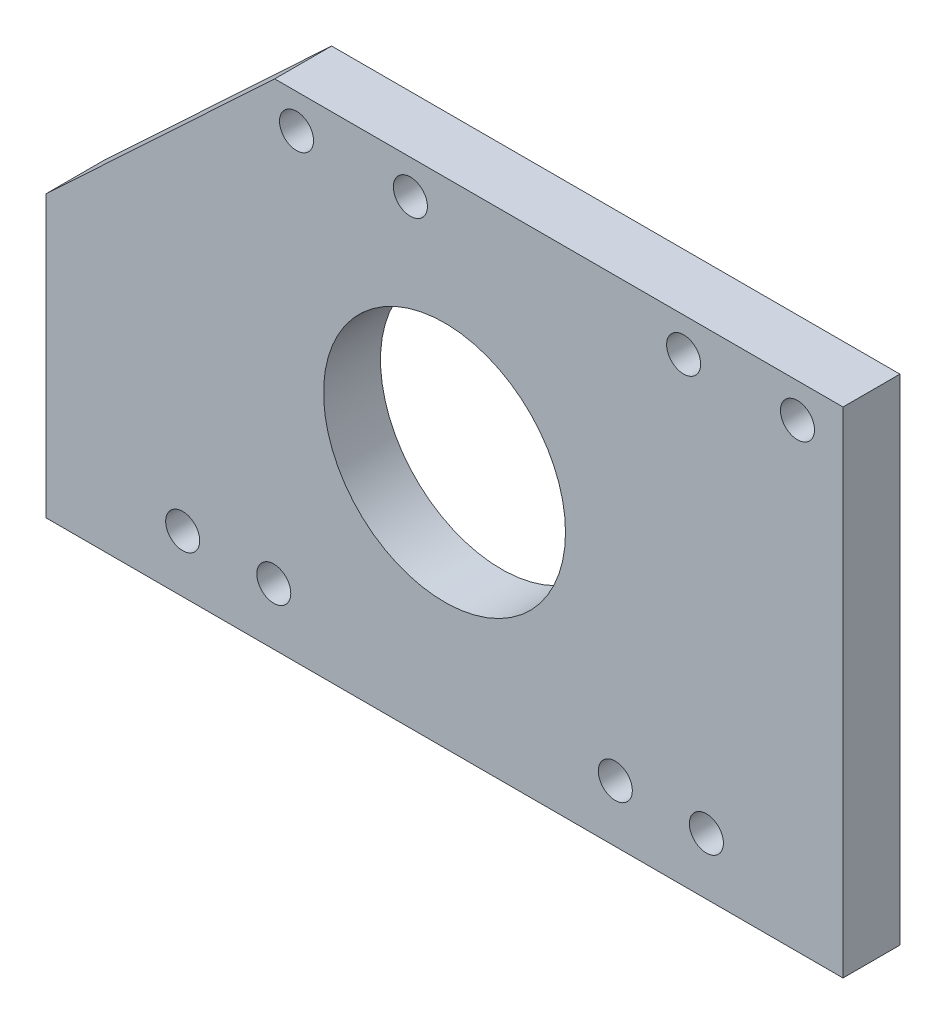
SolidWorks part; units mm, degrees
ref_plane "Front Plane" through (0, 0, 0) normal (0, 0, 1) x (1, 0, 0)
ref_plane "Top Plane" through (0, 0, 0) normal (0, 1, 0) x (1, 0, 0)
ref_plane "Right Plane" through (0, 0, 0) normal (1, 0, 0) x (0, 0, -1)
sketch "Sketch1" plane through (0, 0, 0) normal (0, 0, 1) x (1, 0, 0)
  line L0 (82.55, 0) -> (-82.55, 0)
  line L1 (127, -27.5819) -> (-127, -27.5819)
  line L2 (127, -27.5819) -> (127, 27.5819)
  line L3 (127, 27.5819) -> (-127, 27.5819)
  line L4 (-127, -27.5819) -> (-127, 27.5819)
  line L5 (127, -27.5819) -> (-127, 27.5819) construction
  line L6 (127, 27.5819) -> (-127, -27.5819) construction
  circle A0 centre (-82.55, 0) radius 13.4937
  circle A1 centre (82.55, 0) radius 13.4937
  point P0 (0, 0)
  point P12 (0, 0)
  dimension "D3" = 26.9875
  dimension "D4" = 26.9875
  dimension "D1" = 254
  dimension "D2" = 55.1637
  dimension "D5" = 165.1
extrude "Boss-Extrude1" add sketch "Sketch1" along normal blind 6.35
hole_wizard "#6 Clearance Hole1" positions "Sketch2" profile "Sketch3" hole size "#6" standard "ANSI Inch" end condition through all
sketch "Sketch2" plane through (0, 0, 6.35) normal (0, 0, 1) x (1, 0, 0)
  line L0 (-111.76, -21.2319) -> (-101.6, -21.2319)
  line L2 (-63.5, -21.2319) -> (-53.34, -21.2319)
  line L4 (127, -27.5819) -> (-127, -27.5819) construction
  line L5 (-127, -27.5819) -> (-127, 27.5819) construction
  point P0 (-111.76, -21.2319)
  point P2 (-101.6, -21.2319)
  point P4 (-63.5, -21.2319)
  point P6 (-53.34, -21.2319)
  dimension "D1" = 6.35
  dimension "D2" = 6.35
  dimension "D3" = 10.16
  dimension "D4" = 10.16
  dimension "D5" = 15.24
  dimension "D6" = 63.5
sketch "Sketch3" plane through (-111.76, -21.2319, 6.35) normal (1, 0, 0) x (0, -1, 0)
  line L0 (0, 0) -> (0, 6.35)
  line L1 (0, 6.35) -> (1.8986, 6.35)
  line L2 (1.8986, 6.35) -> (1.8986, 0)
  line L5 (1.8986, 0) -> (0, 0)
  line L11 (0, -6.35) -> (0, 107.95) construction
  dimension "Thru Hole Dia." = 3.7973
  dimension "Thru Hole Depth" = 6.35
ref_plane "Plane1" through (0, 0, 0) normal (-1, 0, 0) x (0, 0, 1)
mirror "Mirror1" about plane through (0, 0, 0) normal (-1, 0, 0) of "#6 Clearance Hole1"
sketch "Sketch4" plane through (0, 0, 6.35) normal (0, 0, 1) x (1, 0, 0)
  line L1 (127, 27.5819) -> (-127, 27.5819) construction
  line L2 (127, -27.5819) -> (-38.1, -27.5819)
  line L3 (127, -27.5819) -> (127, 27.5819)
  line L4 (127, 27.5819) -> (-38.1, 27.5819)
  line L6 (-38.1, -27.5819) -> (-38.1, 27.5819)
  circle A1 centre (-53.34, -21.2319) radius 1.8987 construction
  dimension "D1" = 15.24
extrude "Cut-Extrude1" cut sketch "Sketch4" against normal blind 6.35
sketch "Sketch5" plane through (0, 0, 6.35) normal (0, 0, 1) x (1, 0, 0)
  line L0 (-127, 3.7336) -> (-101.4962, 27.5819)
  line L1 (-127, -27.5819) -> (-127, 27.5819) construction
  line L2 (-38.1, 27.5819) -> (-127, 27.5819) construction
  line L5 (-127, 3.7336) -> (-127, 27.5819)
  line L6 (-127, 27.5819) -> (-101.4962, 27.5819)
extrude "Cut-Extrude2" cut sketch "Sketch5" against normal blind 6.35
hole_wizard "#6 Clearance Hole2" positions "Sketch6" profile "Sketch7" hole size "#6" standard "ANSI Inch" end condition through all
sketch "Sketch6" plane through (0, 0, 6.35) normal (0, 0, 1) x (1, 0, 0)
  line L0 (-55.88, 23.7719) -> (-43.18, 23.7719)
  line L1 (-99.06, 23.7719) -> (-86.36, 23.7719)
  line L3 (-38.1, 27.5819) -> (-101.4962, 27.5819) construction
  line L5 (-38.1, 27.5819) -> (-38.1, -27.5819) construction
  point P0 (-43.18, 23.7719)
  point P2 (-55.88, 23.7719)
  point P9 (-99.06, 23.7719)
  point P11 (-86.36, 23.7719)
  dimension "D1" = 12.7
  dimension "D2" = 12.7
  dimension "D3" = 3.81
  dimension "D4" = 5.08
  dimension "D5" = 30.48
  dimension "D6" = 3.81
sketch "Sketch7" plane through (-43.18, 23.7719, 6.35) normal (1, 0, 0) x (0, -1, 0)
  line L0 (0, 0) -> (0, 6.35)
  line L1 (0, 6.35) -> (1.8986, 6.35)
  line L2 (1.8986, 6.35) -> (1.8986, 0)
  line L5 (1.8986, 0) -> (0, 0)
  line L11 (0, -6.35) -> (0, 107.95) construction
  dimension "Thru Hole Dia." = 3.7973
  dimension "Thru Hole Depth" = 6.35
